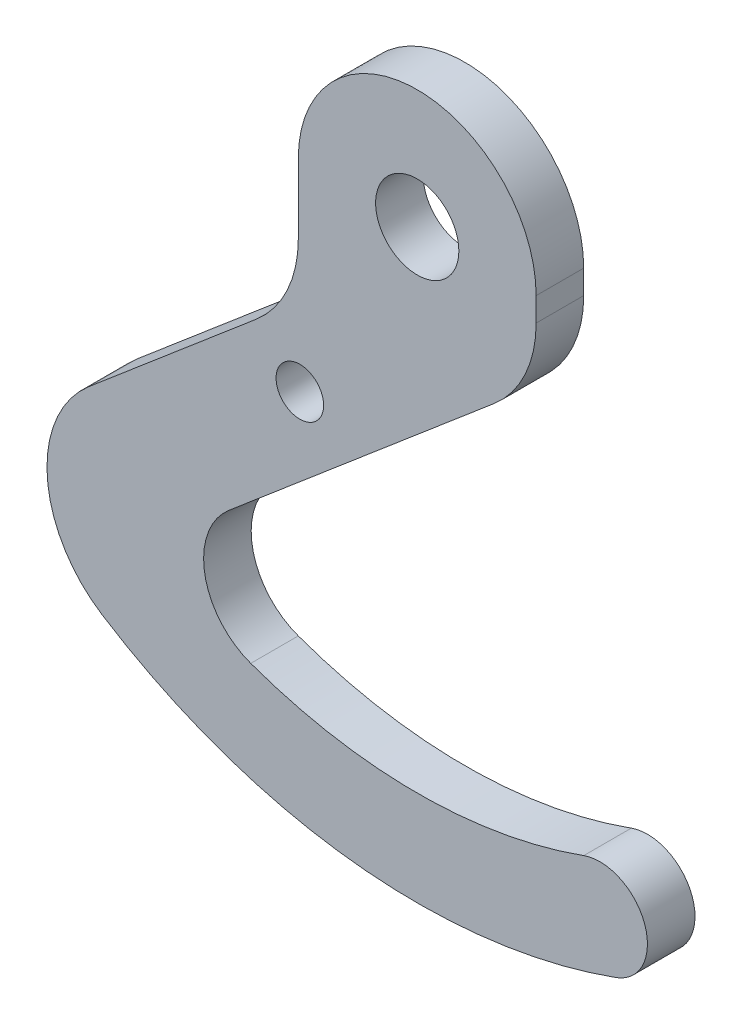
SolidWorks part; units mm, degrees
ref_plane "Front Plane" through (0, 0, 0) normal (0, 0, 1) x (1, 0, 0)
ref_plane "Top Plane" through (0, 0, 0) normal (0, 1, 0) x (1, 0, 0)
ref_plane "Right Plane" through (0, 0, 0) normal (1, 0, 0) x (0, 0, -1)
sketch "Sketch1" plane through (0, 0, 0) normal (0, 0, 1) x (1, 0, 0)
  line L0 (-5, 0) -> (-5, -2.9289)
  line L1 (5, -18) -> (-5, -18) construction
  line L2 (5, -18) -> (5, -20) construction
  line L3 (5, -20) -> (-5, -20) construction
  line L4 (-5, -18) -> (-5, -20) construction
  line L5 (0, -18) -> (0, 0) construction
  line L6 (3.2353, -4.8122) -> (-7.9225, -14.2816)
  line L8 (5, 0) -> (5, -1)
  line L9 (-6.7647, -6.7411) -> (-13.8023, -12.7138)
  line L10 (-4.9357, -8.4678) -> (-9.5493, -12.3833) construction
  line L11 (0, 0) -> (5, 0) construction
  line L12 (-11.167, -10.4772) -> (-7.9317, -14.2894) construction
  arc A0 (-7, -19.3907) -> (7, -19.3907) centre (0, 0) ccw
  arc A1 (-13.2605, -20.7384) -> (8.3582, -23.1531) centre (0, 0) ccw
  arc A2 (8.3582, -23.1531) -> (7, -19.3907) centre (7.6791, -21.2719) ccw
  circle A3 centre (0, 0) radius 1.75
  arc A4 (-7, -19.3907) -> (-7.9225, -14.2816) centre (-5.9814, -16.569) cw
  arc A5 (-13.2605, -20.7384) -> (-13.8023, -12.7138) centre (-10.567, -16.526) cw
  circle A6 centre (0, 0) radius 20.6155 construction
  circle A7 centre (0, 0) radius 24.6155 construction
  arc A8 (3.2353, -4.8122) -> (5, -1) centre (0, -1) ccw
  arc A9 (-6.7647, -6.7411) -> (-5, -2.9289) centre (-10, -2.9289) ccw
  arc A10 (5, 0) -> (-5, 0) centre (0, 0) ccw
  circle A12 centre (-4.9357, -8.4678) radius 1
  point P0 (0, 0)
  point P31 (-5, -5.2434)
  dimension "D4" = 3.5
  dimension "D5" = 3
  dimension "D9" = 2
  dimension "D10" = 5
  dimension "D11" = 5
  dimension "D7" = 1
  dimension "D15" = 5
  dimension "D13" = 2
  dimension "D1" = 10
  dimension "D2" = 2
  dimension "D6" = 5
  dimension "D12" = 2
  dimension "D14" = 20
  dimension "D3" = 4
extrude "Boss-Extrude1" add sketch "Sketch1" along normal mid plane 2
